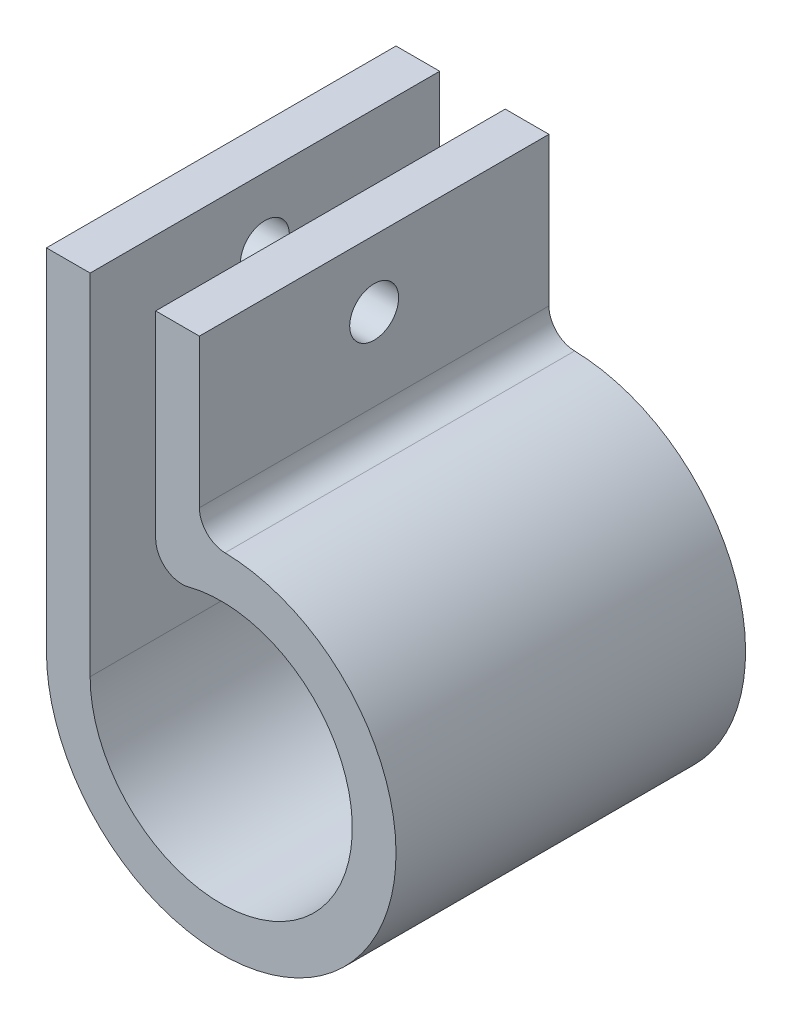
SolidWorks part; units mm, degrees
material "ABS"
ref_plane "Front Plane" through (0, 0, 0) normal (0, 0, 1) x (1, 0, 0)
ref_plane "Top Plane" through (0, 0, 0) normal (0, 1, 0) x (1, 0, 0)
ref_plane "Right Plane" through (0, 0, 0) normal (1, 0, 0) x (0, 0, -1)
sketch "Sketch1" plane through (0, 0, 0) normal (0, 0, 1) x (1, 0, 0)
  line L0 (-19.05, 50.8) -> (-25.4, 50.8)
  line L1 (-25.4, 50.8) -> (-25.4, 0)
  line L2 (-19.05, 50.8) -> (-19.05, 0)
  line L3 (-9.525, 16.4978) -> (-9.525, 50.8)
  line L4 (-9.525, 50.8) -> (-3.175, 50.8)
  line L5 (-3.175, 50.8) -> (-3.175, 25.2008)
  arc A0 (-19.05, 0) -> (-9.525, 16.4978) centre (0, 0) ccw
  arc A1 (-25.4, 0) -> (-3.175, 25.2008) centre (0, 0) ccw
  dimension "D1" = 19.05
  dimension "D3" = 25.4
  dimension "D2" = 9.525
  dimension "D4" = 50.8
  dimension "D5" = 6.35
extrude "Boss-Extrude1" add sketch "Sketch1" along normal mid plane 50.8
fillet "Fillet1" radius 3.81 1 edges at (-9.525, 16.4978, 0)
fillet "Fillet2" radius 3.81 1 edges at (-3.175, 25.2008, 0)
ref_plane "Plane1" through (-25.4, 0, 0) normal (-1, 0, 0) x (0, 0, 1)
sketch "Sketch2" plane through (-25.4, 0, 0) normal (-1, 0, 0) x (0, 0, 1)
  line L0 (25.4, 50.8) -> (-25.4, 50.8) construction
  circle A0 centre (0, 41.148) radius 3.556
  point P4 (0, 0)
  dimension "D1" = 7.112
  dimension "D2" = 9.652
extrude "Cut-Extrude1" cut sketch "Sketch2" against normal through all both and the other way through all
